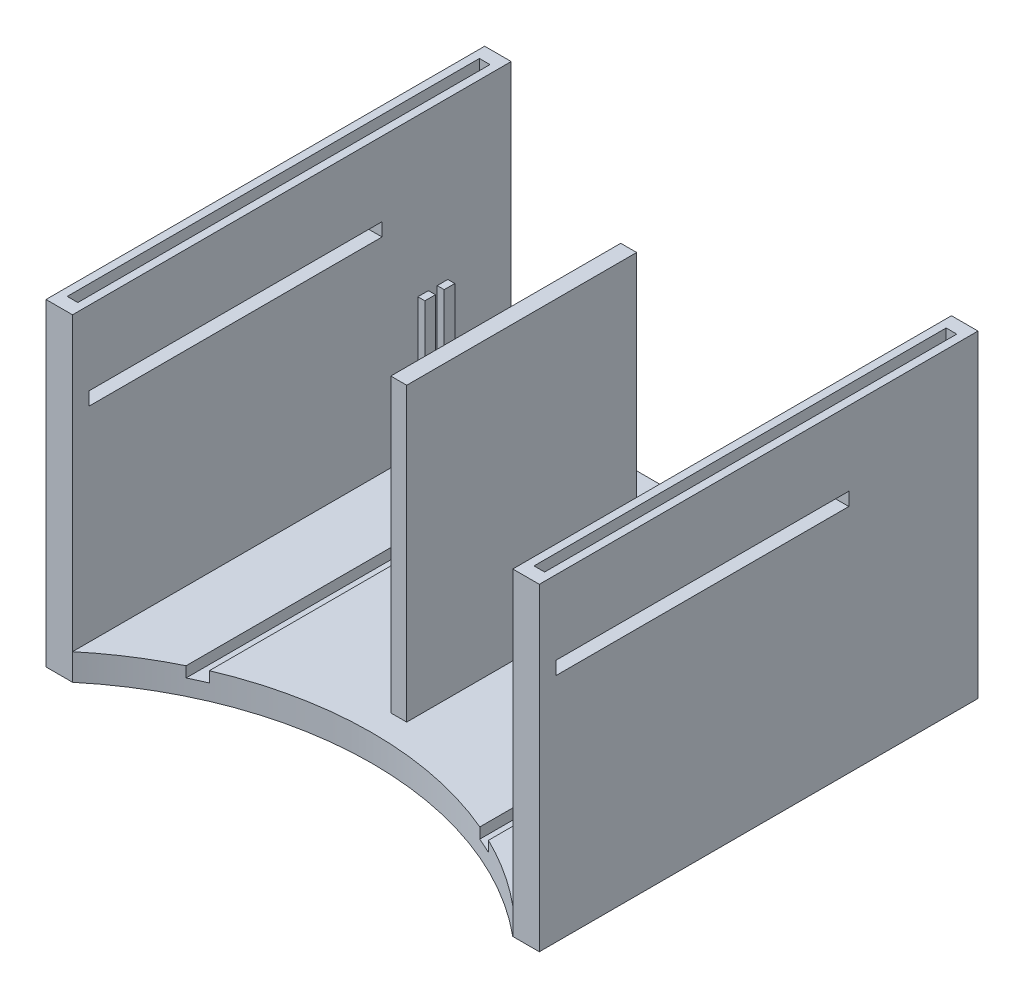
SolidWorks part; units mm, degrees
ref_plane "Front Plane" through (0, 0, 0) normal (0, 0, 1) x (1, 0, 0)
ref_plane "Top Plane" through (0, 0, 0) normal (0, 1, 0) x (1, 0, 0)
ref_plane "Right Plane" through (0, 0, 0) normal (1, 0, 0) x (0, 0, -1)
sketch "Sketch2" plane through (0, 0, 0) normal (0, 0, 1) x (1, 0, 0)
  line L0 (0, 0) -> (186, 0)
  line L1 (186, 0) -> (186, 120)
  line L2 (0, 0) -> (0, 120)
  dimension "D1" = 120
  dimension "D2" = 186
extrude "Extrude-Thin2" add sketch "Sketch2" along normal blind 165.4 thin thin type one direction wall 10
sketch "Sketch11" plane through (0, 10, 0) normal (0, 1, 0) x (1, 0, 0)
  line L0 (10, -165.4) -> (10, 0) construction
  line L1 (11.5, -32.703) -> (174.5, -32.703)
  line L2 (11.5, -32.703) -> (11.5, -36.703)
  line L3 (11.5, -36.703) -> (174.5, -36.703)
  line L4 (174.5, -32.703) -> (174.5, -36.703)
  line L6 (176, 0) -> (10, 0) construction
  dimension "D1" = 32.703
  dimension "D2" = 4
  dimension "D3" = 163
  dimension "D4" = 1.5
extrude "Boss-Extrude3" add sketch "Sketch11" along normal blind 2.6416
sketch "Sketch13" plane through (10, 0, 0) normal (1, 0, 0) x (0, 0, -1)
  line L0 (0, 120) -> (0, 0) construction
  line L1 (-159.195, 92.0516) -> (-48.7, 92.0516)
  line L2 (-159.195, 92.0516) -> (-159.195, 87.0516)
  line L3 (-159.195, 87.0516) -> (-48.7, 87.0516)
  line L4 (-48.7, 92.0516) -> (-48.7, 87.0516)
  line L6 (-165.4, 120) -> (-165.4, 0) construction
  line L7 (-165.4, 120) -> (0, 120) construction
  dimension "D1" = 5
  dimension "D2" = 6.205
  dimension "D3" = 48.7
  dimension "D4" = 27.9484
extrude "Cut-Extrude6" cut sketch "Sketch13" against normal through all both and the other way through all
sketch "Sketch14" plane through (0, 10, 0) normal (0, 1, 0) x (1, 0, 0)
  line L0 (176, -165.4) -> (10, -165.4)
  line L1 (93, -135.4) -> (10, -135.4) construction
  line L2 (10, -165.4) -> (10, 0) construction
  arc A0 (10, -165.4) -> (176, -165.4) centre (93, -265.2167) cw
  dimension "D1" = 30
extrude "Cut-Extrude7" cut sketch "Sketch14" against normal through all
sketch "Sketch19" plane through (0, 120, 0) normal (0, 1, 0) x (1, 0, 0)
  line L0 (10, -165.4) -> (10, 0) construction
  line L1 (3, -5) -> (7, -5)
  line L2 (3, -5) -> (3, -160.4)
  line L3 (3, -160.4) -> (7, -160.4)
  line L4 (7, -5) -> (7, -160.4)
  line L5 (0, -165.4) -> (0, 0) construction
  line L6 (0, 0) -> (10, 0) construction
  line L7 (0, -165.4) -> (10, -165.4) construction
  point P9 (5, 0)
  point P12 (5, -165.4)
  dimension "D1" = 3
  dimension "D2" = 3
  dimension "D3" = 5
  dimension "D4" = 5
extrude "Cut-Extrude9" cut sketch "Sketch19" against normal blind 10
sketch "Sketch20" plane through (0, 120, 0) normal (0, 1, 0) x (1, 0, 0)
  line L0 (186, -165.4) -> (186, 0) construction
  line L1 (179, -5) -> (183, -5)
  line L2 (179, -5) -> (179, -160.4)
  line L3 (179, -160.4) -> (183, -160.4)
  line L4 (183, -5) -> (183, -160.4)
  line L5 (176, -165.4) -> (176, 0) construction
  line L6 (176, 0) -> (186, 0) construction
  line L7 (176, -165.4) -> (186, -165.4) construction
  point P9 (181, 0)
  point P12 (181, -165.4)
  dimension "D1" = 3
  dimension "D2" = 3
  dimension "D3" = 5
  dimension "D4" = 5
extrude "Cut-Extrude10" cut sketch "Sketch20" against normal blind 10
sketch "Sketch21" plane through (0, 10, 0) normal (0, 1, 0) x (1, 0, 0)
  line L0 (176, -165.4) -> (176, 0) construction
  line L1 (90, -38.703) -> (96, -38.703)
  line L2 (90, -38.703) -> (90, -125.4)
  line L3 (90, -125.4) -> (96, -125.4)
  line L4 (96, -38.703) -> (96, -125.4)
  line L5 (10, -165.4) -> (10, 0) construction
  line L7 (10, -159.195) -> (10, -48.7) construction
  line L8 (10, -119.195) -> (176, -119.195) construction
  line L9 (10, -165.4) -> (10, 0) construction
  line L10 (0, -165.4) -> (10, -165.4) construction
  line L11 (11.5, -36.703) -> (174.5, -36.703) construction
  dimension "D1" = 80
  dimension "D2" = 80
  dimension "D3" = 40
  dimension "D4" = 46.205
  dimension "D5" = 2
extrude "Boss-Extrude4" add sketch "Sketch21" along direction (0, 1, 0) on the side of the normal through all
sketch "Sketch22" plane through (0, 10, 0) normal (0, 1, 0) x (1, 0, 0)
  line L0 (36, -48.703) -> (36, -148.5832)
  line L1 (36, -148.5832) -> (42, -145.8376)
  line L2 (42, -145.8376) -> (42, -48.703)
  line L3 (42, -48.703) -> (36, -48.703)
  line L4 (11.5, -36.703) -> (174.5, -36.703) construction
  line L6 (10, -159.195) -> (10, -48.7) construction
  line L7 (144, -145.8376) -> (150, -148.5832)
  line L8 (150, -148.5832) -> (150, -48.703)
  line L9 (150, -48.703) -> (144, -48.703)
  line L10 (144, -48.703) -> (144, -145.8376)
  line L11 (176, -165.4) -> (176, 0) construction
  arc A0 (176, -165.4) -> (10, -165.4) centre (93, -265.2167) ccw construction
  dimension "D1" = 6
  dimension "D2" = 26
  dimension "D3" = 6
  dimension "D4" = 26
  dimension "D5" = 12
extrude "Cut-Extrude11" cut sketch "Sketch22" against normal blind 4
sketch "Sketch23" plane through (0, 10, 0) normal (0, 1, 0) x (1, 0, 0)
  line L0 (10, -165.4) -> (10, 0) construction
  line L1 (11.5, -25.4) -> (174.5, -25.4)
  line L2 (11.5, -25.4) -> (11.5, -29.4)
  line L3 (11.5, -29.4) -> (174.5, -29.4)
  line L4 (174.5, -25.4) -> (174.5, -29.4)
  line L5 (176, -165.4) -> (176, 0) construction
  line L8 (174.5, -32.703) -> (11.5, -32.703) construction
  dimension "D1" = 3.303
  dimension "D2" = 1.5
  dimension "D3" = 1.5
  dimension "D4" = 4
extrude "Boss-Extrude5" add sketch "Sketch23" along normal blind 2.6416
sketch "Sketch24" plane through (0, 12.6416, 0) normal (0, 1, 0) x (1, 0, 0)
  line L0 (11.5, -36.703) -> (174.5, -36.703) construction
  line L1 (11.5, -32.703) -> (14.1416, -32.703)
  line L2 (11.5, -32.703) -> (11.5, -36.703)
  line L3 (11.5, -36.703) -> (14.1416, -36.703)
  line L4 (14.1416, -32.703) -> (14.1416, -36.703)
  dimension "D1" = 2.6416
extrude "Boss-Extrude6" add sketch "Sketch24" along normal blind 49.6416
sketch "Sketch25" plane through (0, 12.6416, 0) normal (0, 1, 0) x (1, 0, 0)
  line L0 (11.5, -29.4) -> (174.5, -29.4) construction
  line L1 (11.5, -25.4) -> (14.14, -25.4)
  line L2 (11.5, -25.4) -> (11.5, -29.4)
  line L3 (11.5, -29.4) -> (14.14, -29.4)
  line L4 (14.14, -25.4) -> (14.14, -29.4)
  dimension "D1" = 2.64
extrude "Boss-Extrude7" add sketch "Sketch25" along normal blind 49.6416
sketch "Sketch26" plane through (0, 12.6416, 0) normal (0, 1, 0) x (1, 0, 0)
  line L0 (14.1416, -36.703) -> (174.5, -36.703) construction
  line L1 (174.5, -32.703) -> (171.86, -32.703)
  line L2 (174.5, -32.703) -> (174.5, -36.703)
  line L3 (174.5, -36.703) -> (171.86, -36.703)
  line L4 (171.86, -32.703) -> (171.86, -36.703)
  line L5 (174.5, -29.4) -> (174.5, -25.4) construction
  line L6 (174.5, -25.4) -> (171.86, -25.4)
  line L7 (174.5, -25.4) -> (174.5, -29.4)
  line L8 (174.5, -29.4) -> (171.86, -29.4)
  line L9 (171.86, -25.4) -> (171.86, -29.4)
  line L10 (174.5, -29.4) -> (174.5, -25.4) construction
  line L11 (14.14, -29.4) -> (174.5, -29.4) construction
  dimension "D1" = 2.64
  dimension "D2" = 2.64
extrude "Boss-Extrude8" add sketch "Sketch26" along normal blind 49.6416
